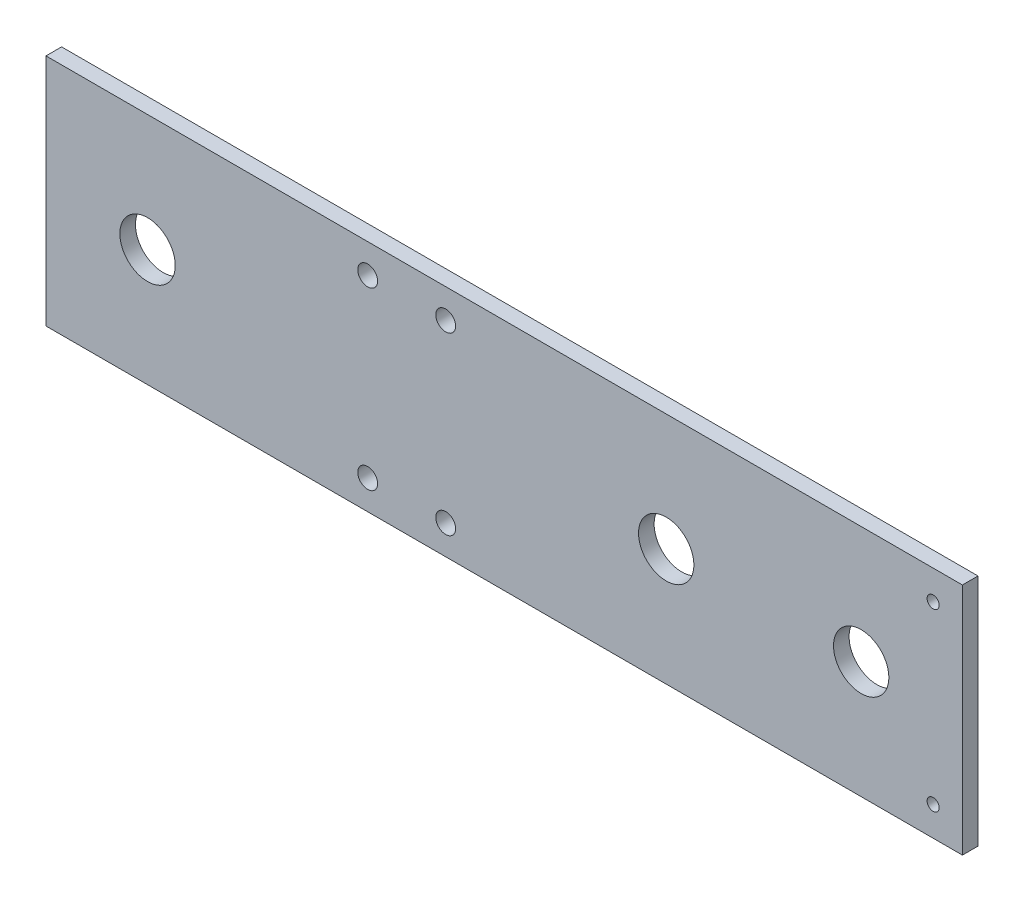
SolidWorks part; units mm, degrees
ref_plane "Front Plane" through (0, 0, 0) normal (0, 0, 1) x (1, 0, 0)
ref_plane "Top Plane" through (0, 0, 0) normal (0, 1, 0) x (1, 0, 0)
ref_plane "Right Plane" through (0, 0, 0) normal (1, 0, 0) x (0, 0, -1)
sketch "Sketch1" plane through (0, 0, 0) normal (0, 0, 1) x (1, 0, 0)
  line L0 (75.9587, -30) -> (75.9587, 30) construction
  line L1 (75.9587, -30) -> (-159.0413, -30)
  line L2 (75.9587, -30) -> (75.9587, 30)
  line L3 (75.9587, 30) -> (-159.0413, 30)
  line L4 (-159.0413, -30) -> (-159.0413, 30)
  line L5 (-284.0413, -30) -> (75.9587, -30) construction
  line L6 (75.9587, 30) -> (-284.0413, 30) construction
  circle A0 centre (-133, 0) radius 7.1 construction
  circle A1 centre (50, 0) radius 7.1 construction
  circle A2 centre (0, 0) radius 7.1 construction
  circle A3 centre (-133, 0) radius 7.1
  circle A4 centre (50, 0) radius 7.1
  circle A5 centre (0, 0) radius 7.1
  circle A6 centre (68.4514, -22.4927) radius 1.55 construction
  circle A7 centre (68.4514, 22.4927) radius 1.55 construction
  circle A8 centre (68.4514, -22.4927) radius 1.55
  circle A9 centre (68.4514, 22.4927) radius 1.55
  circle A10 centre (-56.5486, -22.4927) radius 2.55 construction
  circle A11 centre (-56.5486, 22.4927) radius 2.55 construction
  circle A12 centre (-56.5486, -22.4927) radius 2.55
  circle A13 centre (-56.5486, 22.4927) radius 2.55
  circle A14 centre (-76.5486, -22.4927) radius 2.55 construction
  circle A15 centre (-76.5486, -22.4927) radius 2.55
  circle A16 centre (-76.5486, 22.4927) radius 2.55 construction
  circle A17 centre (-76.5486, 22.4927) radius 2.55
  dimension "D1" = 235
extrude "Boss-Extrude1" add sketch "Sketch1" along normal blind 4
